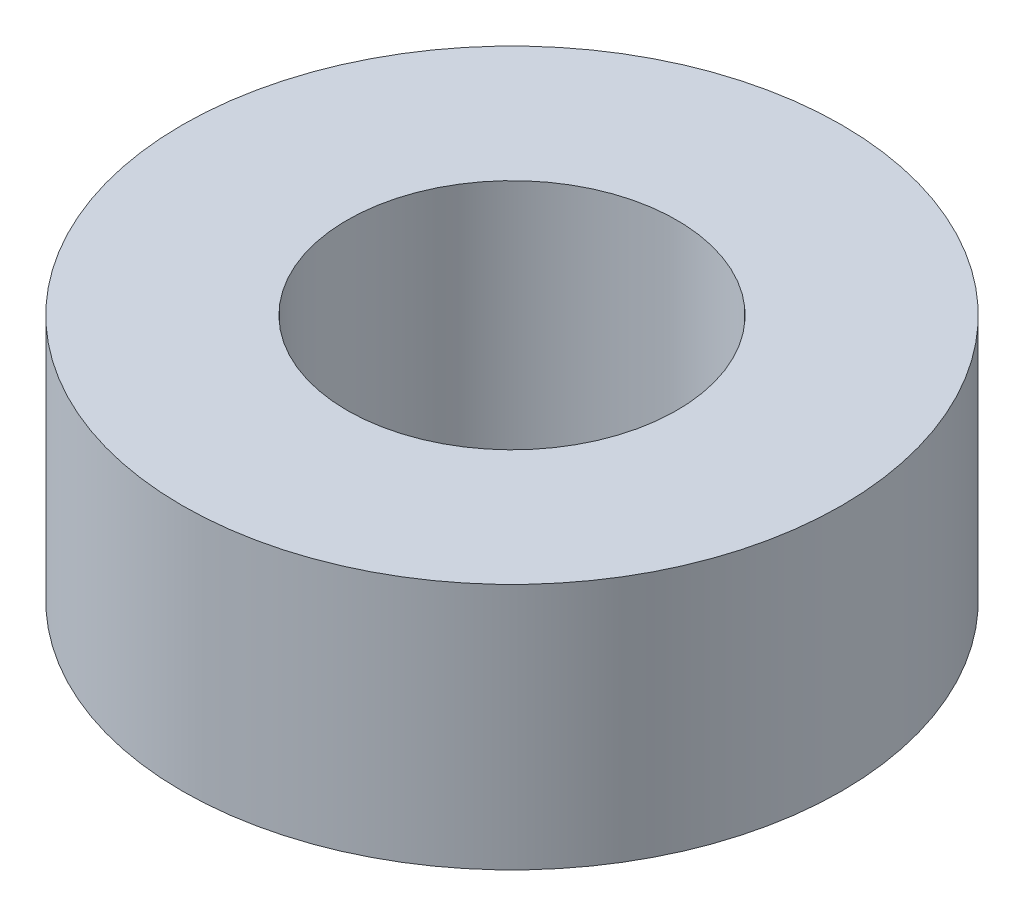
SolidWorks part; units mm, degrees
ref_plane "Front Plane" through (0, 0, 0) normal (0, 0, 1) x (1, 0, 0)
ref_plane "Top Plane" through (0, 0, 0) normal (0, 1, 0) x (1, 0, 0)
ref_plane "Right Plane" through (0, 0, 0) normal (1, 0, 0) x (0, 0, -1)
sketch "Sketch1" plane through (0, 0, 0) normal (0, 1, 0) x (1, 0, 0)
  circle A0 centre (0, 0) radius 2
  circle A1 centre (0, 0) radius 4
  dimension "D1" = 8
  dimension "D2" = 4
extrude "Boss-Extrude1" add sketch "Sketch1" along normal blind 3
